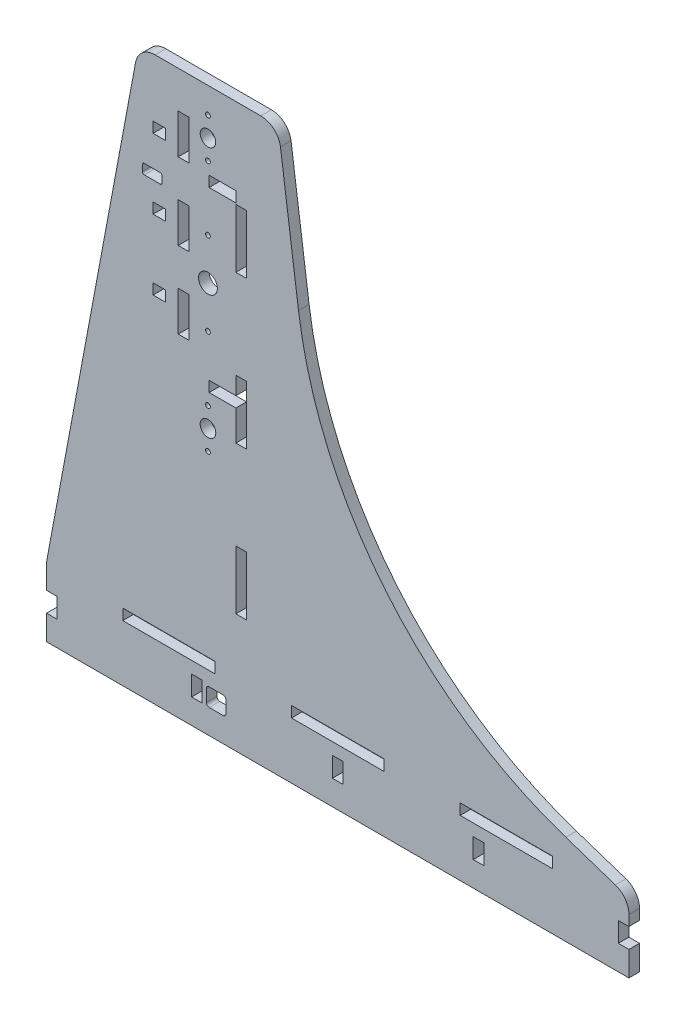
SolidWorks part; units mm, degrees
ref_plane "Front Plane" through (0, 0, 0) normal (0, 0, 1) x (1, 0, 0)
ref_plane "Top Plane" through (0, 0, 0) normal (0, 1, 0) x (1, 0, 0)
ref_plane "Right Plane" through (0, 0, 0) normal (1, 0, 0) x (0, 0, -1)
sketch "Model" plane through (0, 0, 0) normal (0, 0, 1) x (1, 0, 0)
  line L91 (-147, 22.5) -> (-147, 33.91)
  line L92 (-147, 0) -> (147, 0)
  line L93 (-147, 0) -> (-147, 12.5)
  line L94 (-23.334, 34) -> (23.332, 34)
  line L95 (147, 0) -> (147, 12.5)
  line L96 (-147, 12.5) -> (-141.65, 12.5)
  line L97 (147, 22.5) -> (147, 27.7919)
  line L98 (-147, 22.5) -> (-141.65, 22.5)
  line L99 (-141.65, 12.5) -> (-141.65, 22.5)
  line L100 (147, 12.5) -> (141.65, 12.5)
  line L101 (-102.0203, 275.8347) -> (-146.8303, 35.7447)
  line L102 (147, 22.5) -> (141.65, 22.5)
  line L103 (141.65, 12.5) -> (141.65, 22.5)
  line L104 (140.1623, 37.2788) -> (115.1407, 45.6192)
  line L105 (-28.8912, 275.3472) -> (-19.7908, 208.4121)
  line L106 (-92.19, 284) -> (-38.8, 284)
  line L107 (-108.5, 34) -> (-61.834, 34)
  line L108 (-108.5, 34) -> (-108.5, 28.5)
  line L109 (-108.5, 28.5) -> (-61.834, 28.5)
  line L110 (-61.834, 34) -> (-61.834, 28.5)
  line L111 (-23.334, 34) -> (-23.334, 28.5)
  line L112 (-23.334, 28.5) -> (23.332, 28.5)
  line L113 (23.332, 34) -> (23.332, 28.5)
  line L114 (61.832, 34) -> (108.498, 34)
  line L115 (61.832, 34) -> (61.832, 28.5)
  line L116 (61.832, 28.5) -> (108.498, 28.5)
  line L117 (108.498, 34) -> (108.498, 28.5)
  line L118 (-2.67, 22.5) -> (2.68, 22.5)
  line L119 (-73.75, 12.5) -> (-68.4, 12.5)
  line L120 (-73.75, 12.5) -> (-73.75, 22.5)
  line L121 (-73.75, 22.5) -> (-68.4, 22.5)
  line L122 (-68.4, 12.5) -> (-68.4, 22.5)
  line L123 (2.68, 12.5) -> (2.68, 22.5)
  line L124 (-2.67, 12.5) -> (-2.67, 22.5)
  line L125 (-2.67, 12.5) -> (2.68, 12.5)
  line L126 (68.41, 22.5) -> (73.76, 22.5)
  line L127 (73.76, 12.5) -> (73.76, 22.5)
  line L128 (68.41, 12.5) -> (68.41, 22.5)
  line L129 (68.41, 12.5) -> (73.76, 12.5)
  line L130 (-93.2, 219.175) -> (-86.85, 219.175)
  line L131 (-64.85, 21.33) -> (-57.85, 21.33)
  line L132 (-66.35, 19.83) -> (-66.35, 13.83)
  line L133 (-64.85, 12.33) -> (-57.85, 12.33)
  line L134 (-56.35, 19.83) -> (-56.35, 13.83)
  line L135 (-93.2, 254.525) -> (-86.85, 254.525)
  line L136 (-93.2, 254.525) -> (-93.2, 249.175)
  line L137 (-93.2, 249.175) -> (-86.85, 249.175)
  line L138 (-86.85, 254.525) -> (-86.85, 249.175)
  line L139 (-93.2, 219.175) -> (-93.2, 213.825)
  line L140 (-93.2, 213.825) -> (-86.85, 213.825)
  line L141 (-86.85, 219.175) -> (-86.85, 213.825)
  line L142 (-93.2, 183.825) -> (-86.85, 183.825)
  line L143 (-93.2, 183.825) -> (-93.2, 178.475)
  line L144 (-93.2, 178.475) -> (-86.85, 178.475)
  line L145 (-86.85, 183.825) -> (-86.85, 178.475)
  line L146 (-75.15, 226.5) -> (-75.15, 206.5)
  line L147 (-80.5, 265.25) -> (-75.15, 265.25)
  line L148 (-80.5, 265.25) -> (-80.5, 245.25)
  line L149 (-80.5, 245.25) -> (-75.15, 245.25)
  line L150 (-75.15, 265.25) -> (-75.15, 245.25)
  line L151 (-80.5, 206.5) -> (-75.15, 206.5)
  line L152 (-80.5, 226.5) -> (-80.5, 206.5)
  line L153 (-80.5, 226.5) -> (-75.15, 226.5)
  line L154 (-75.15, 187.75) -> (-75.15, 167.75)
  line L155 (-80.5, 167.75) -> (-75.15, 167.75)
  line L156 (-80.5, 187.75) -> (-80.5, 167.75)
  line L157 (-80.5, 187.75) -> (-75.15, 187.75)
  line L158 (-51.4, 164.334) -> (-46.05, 164.334)
  line L159 (-89.595, 228.801) -> (-97.595, 228.801)
  line L160 (-88.595, 229.801) -> (-88.595, 232.801)
  line L161 (-89.595, 233.801) -> (-97.595, 233.801)
  line L162 (-98.595, 229.801) -> (-98.595, 232.801)
  line L163 (-51.4, 239) -> (-46.05, 239)
  line L164 (-51.4, 239) -> (-51.4, 209.334)
  line L165 (-51.4, 209.334) -> (-46.05, 209.334)
  line L166 (-46.05, 239) -> (-46.05, 209.334)
  line L167 (-51.4, 164.334) -> (-51.4, 155.351)
  line L168 (-51.4, 134.668) -> (-46.05, 134.668)
  line L169 (-46.05, 164.334) -> (-46.05, 134.668)
  line L170 (-51.4, 89.668) -> (-46.05, 89.668)
  line L171 (-51.4, 89.668) -> (-51.4, 60.002)
  line L172 (-51.4, 60.002) -> (-46.05, 60.002)
  line L173 (-46.05, 89.668) -> (-46.05, 60.002)
  line L174 (-65.5, 261) -> (-65.5, 271) construction
  line L175 (-65.5, 261) -> (-65.5, 251) construction
  line L176 (-51.4, 150.001) -> (-51.4, 134.668)
  line L177 (-51.4, 239.65) -> (-64.9, 239.65)
  line L178 (-51.4, 239.65) -> (-51.4, 245)
  line L179 (-51.4, 245) -> (-64.9, 245)
  line L180 (-64.9, 239.65) -> (-64.9, 245)
  line L181 (-64.9, 155.351) -> (-51.4, 155.351)
  line L182 (-64.9, 155.351) -> (-64.9, 150.001)
  line L183 (-64.9, 150.001) -> (-51.4, 150.001)
  line L184 (-65.5, 197.5) -> (-65.5, 218.5) construction
  line L185 (-65.5, 197.5) -> (-65.5, 176.5) construction
  line L186 (-65.5, 134.001) -> (-65.5, 144.001) construction
  line L187 (-65.5, 134.001) -> (-65.5, 124.001) construction
  arc A22 (147, 27.7919) -> (140.1623, 37.2788) centre (137, 27.7919) ccw
  arc A23 (-146.8303, 35.7447) -> (-147, 33.91) centre (-137, 33.91) ccw
  arc A24 (-92.19, 284) -> (-102.0203, 275.8347) centre (-92.19, 274) ccw
  arc A25 (-28.8912, 275.3472) -> (-38.8, 284) centre (-38.8, 274) ccw
  arc A26 (-19.7908, 208.4121) -> (115.1407, 45.6192) centre (178.386, 235.356) ccw
  arc A27 (-64.85, 21.33) -> (-66.35, 19.83) centre (-64.85, 19.83) ccw
  arc A28 (-56.35, 19.83) -> (-57.85, 21.33) centre (-57.85, 19.83) ccw
  arc A29 (-57.85, 12.33) -> (-56.35, 13.83) centre (-57.85, 13.83) ccw
  arc A30 (-66.35, 13.83) -> (-64.85, 12.33) centre (-64.85, 13.83) ccw
  arc A31 (-97.595, 233.801) -> (-98.595, 232.801) centre (-97.595, 232.801) ccw
  arc A32 (-98.595, 229.801) -> (-97.595, 228.801) centre (-97.595, 229.801) ccw
  arc A33 (-89.595, 228.801) -> (-88.595, 229.801) centre (-89.595, 229.801) ccw
  arc A34 (-88.595, 232.801) -> (-89.595, 233.801) centre (-89.595, 232.801) ccw
  circle A35 centre (-65.5, 261) radius 3.915
  circle A36 centre (-65.5, 271) radius 1.2
  circle A37 centre (-65.5, 251) radius 1.2
  circle A38 centre (-65.5, 197.5) radius 4.75
  circle A39 centre (-65.5, 218.5) radius 1.2
  circle A40 centre (-65.5, 176.5) radius 1.2
  circle A41 centre (-65.5, 134.001) radius 3.95
  circle A42 centre (-65.5, 144.001) radius 1.2
  circle A43 centre (-65.5, 124.001) radius 1.2
  dimension "D16" = 200
  dimension "D18" = 10
  dimension "D6" = 1.5
  dimension "D13" = 1
  dimension "D42" = 7.83
  dimension "D58" = 2.4
  dimension "D71" = 9.5
  dimension "D76" = 2.4
  dimension "D80" = 7.9
  dimension "D83" = 2.4
  dimension "D3" = 294
  dimension "D5" = 5.35
  dimension "D11" = 10
  dimension "D12" = 12.5
  dimension "D14" = 284
  dimension "D19" = 53.39
  dimension "D24" = 26.375
  dimension "D27" = 235.356
  dimension "D26" = 31.386
  dimension "D30" = 10
  dimension "D31" = 10
  dimension "D21" = 33.91
  dimension "D33" = 54.81
  dimension "D36" = 28.5
  dimension "D38" = 38.5
  dimension "D39" = 46.666
  dimension "D41" = 5.5
  dimension "D44" = 38.5
  dimension "D48" = 67.9
  dimension "D52" = 65.73
  dimension "D7" = 10
  dimension "D8" = 9
  dimension "D17" = 12.33
  dimension "D22" = 2.05
  dimension "D45" = 6.35
  dimension "D46" = 5.35
  dimension "D47" = 29.475
  dimension "D53" = 53.8
  dimension "D55" = 30
  dimension "D56" = 5.35
  dimension "D57" = 20
  dimension "D25" = 10.725
  dimension "D29" = 6.35
  dimension "D35" = 18.75
  dimension "D15" = 5
  dimension "D20" = 10
  dimension "D34" = 5.395
  dimension "D37" = 9.626
  dimension "D50" = 5.35
  dimension "D51" = 29.666
  dimension "D59" = 6.25
  dimension "D61" = 23.75
  dimension "D64" = 45
  dimension "D63" = 23
  dimension "D67" = 10
  dimension "D10" = 9.65
  dimension "D23" = 5.35
  dimension "D28" = 6
  dimension "D65" = 13.5
  dimension "D66" = 5.35
  dimension "D69" = 15.333
  dimension "D73" = 9
  dimension "D75" = 9.65
  dimension "D78" = 21
  dimension "D85" = 10
  dimension "D40" = 14.1
  dimension "D68" = 16
  dimension "D43" = 3
  dimension "D49" = 3
  dimension "D54" = 3
  dimension "D32" = 3
  dimension "D62" = 3
extrude "Boss-Extrude1" add sketch "Model" along normal blind 5.35
equation "\"mdfthick\"=5.35"
equation "\"D5@Model\"=\"mdfthick\""
equation "\"D46@Model\"=\"mdfthick\""
equation "\"D56@Model\"=\"mdfthick\""
equation "\"D50@Model\"=\"mdfthick\""
equation "\"D23@Model\"=\"mdfthick\""
equation "\"D66@Model\"=\"mdfthick\""
equation "\"D1@Boss-Extrude1\"=\"mdfthick\""
